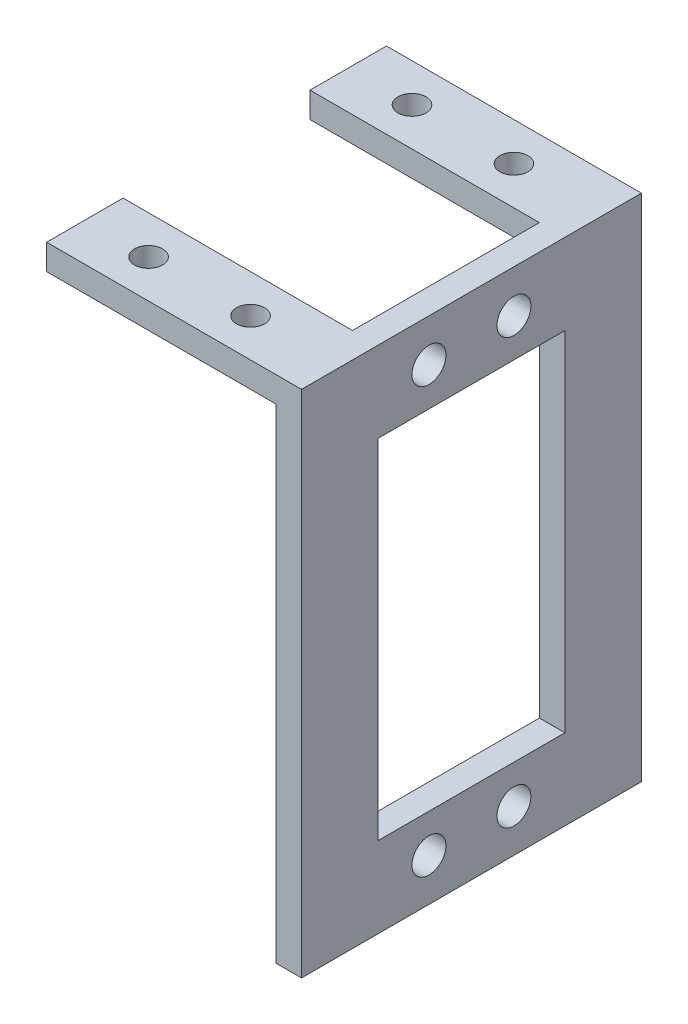
SolidWorks part; units mm, degrees
material "PMMA"
ref_plane "前视基准面" through (0, 0, 0) normal (0, 0, 1) x (1, 0, 0)
ref_plane "上视基准面" through (0, 0, 0) normal (0, 1, 0) x (1, 0, 0)
ref_plane "右视基准面" through (0, 0, 0) normal (1, 0, 0) x (0, 0, -1)
sketch "草图1" plane through (0, 0, 0) normal (0, 0, 1) x (1, 0, 0)
  line L0 (0, 0) -> (30, 0)
  line L1 (30, 0) -> (30, -60)
  line L2 (0, -3) -> (27, -3)
  line L3 (27, -3) -> (27, -60)
  line L4 (27, -60) -> (30, -60)
  line L5 (0, 0) -> (0, -3)
  dimension "D1" = 30
  dimension "D3" = 60
  dimension "D2" = 3
extrude "凸台-拉伸1" add sketch "草图1" along normal blind 40
sketch "草图2" plane through (0, 0, 0) normal (0, 1, 0) x (1, 0, 0)
  line L0 (0, 0) -> (0, -9) construction
  line L1 (0, -40) -> (0, 0) construction
  line L2 (0, -9) -> (27, -9)
  line L3 (30, -40) -> (30, 0) construction
  line L4 (27, -9) -> (27, 0) construction
  line L5 (27, 0) -> (0, 0) construction
  line L6 (0, -20) -> (30, -20) construction
  line L7 (27, -31) -> (27, -40) construction
  line L8 (0, -31) -> (27, -31)
  line L9 (0, -40) -> (0, -31) construction
  line L10 (27, -40) -> (0, -40) construction
  line L11 (27, -40) -> (27, 0) construction
  line L12 (27, -9) -> (27, -31)
  line L13 (0, -9) -> (0, -31)
  line L14 (7.5, -4.5) -> (19.5, -4.5) construction
  line L15 (13.5, -4.5) -> (13.5, 0) construction
  line L16 (13.5, -4.5) -> (13.5, -9) construction
  circle A0 centre (7.5, -4.5) radius 1.65
  circle A1 centre (19.5, -4.5) radius 1.65
  circle A2 centre (19.5, -35.5) radius 1.65
  circle A3 centre (7.5, -35.5) radius 1.65
  dimension "D2" = 3.3
  dimension "D3" = 12
  dimension "D1" = 9
extrude "切除-拉伸2" cut sketch "草图2" against normal blind 10
sketch "草图3" plane through (30, 0, 0) normal (1, 0, 0) x (0, 0, -1)
  line L0 (-20, 0) -> (-20, -71.9676) construction
  line L1 (-40, 0) -> (0, 0) construction
  line L2 (-25, -5) -> (-15, -5) construction
  line L3 (-40, -3) -> (-31, -3) construction
  line L4 (-15, -5) -> (-15, -55) construction
  line L5 (-15, -30) -> (-20, -30) construction
  line L7 (-31, -50.5) -> (-9, -50.5)
  line L8 (-31, -50.5) -> (-31, -9.5)
  line L9 (-31, -9.5) -> (-9, -9.5)
  line L10 (-9, -50.5) -> (-9, -9.5)
  line L11 (-31, -50.5) -> (-9, -9.5) construction
  line L12 (-31, -9.5) -> (-9, -50.5) construction
  circle A0 centre (-25, -5) radius 2
  circle A1 centre (-15, -5) radius 2
  circle A2 centre (-15, -55) radius 2
  circle A3 centre (-25, -55) radius 2
  dimension "D3" = 4
  dimension "D4" = 50
  dimension "D1" = 10
  dimension "D2" = 2
  dimension "D5" = 22
  dimension "D6" = 41
extrude "切除-拉伸3" cut sketch "草图3" against normal blind 10
